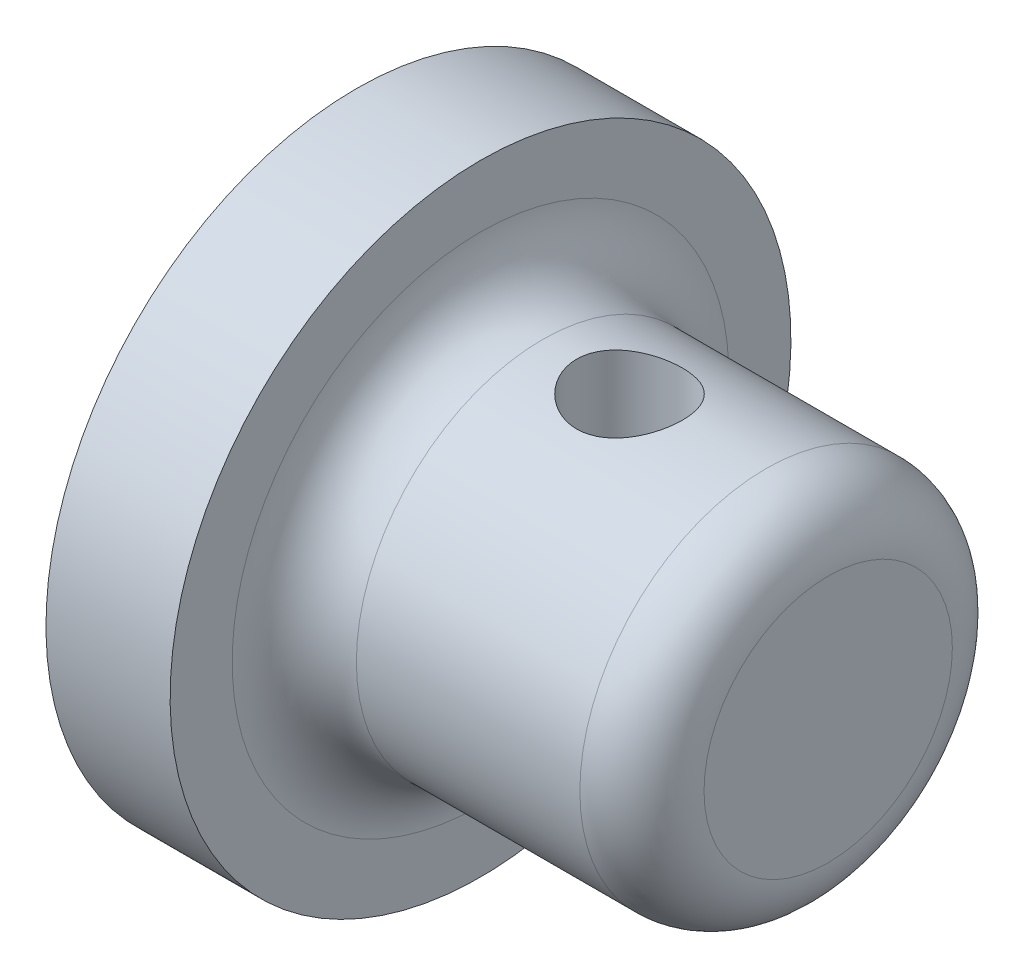
SolidWorks part; units mm, degrees
material "6061 Alloy"
ref_plane "Front Plane" through (0, 0, 0) normal (0, 0, 1) x (1, 0, 0)
ref_plane "Top Plane" through (0, 0, 0) normal (0, 1, 0) x (1, 0, 0)
ref_plane "Right Plane" through (0, 0, 0) normal (1, 0, 0) x (0, 0, -1)
sketch "Sketch1" plane through (0, 0, 0) normal (0, 0, 1) x (1, 0, 0)
  line L0 (0, 0) -> (0, 15.875)
  line L1 (0, 15.875) -> (6.35, 15.875)
  line L2 (6.35, 15.875) -> (6.35, 12.7)
  line L3 (9.525, 9.525) -> (20.955, 9.525)
  line L4 (24.13, 6.35) -> (24.13, 0)
  line L5 (24.13, 0) -> (0, 0)
  arc A0 (6.35, 12.7) -> (9.525, 9.525) centre (9.525, 12.7) ccw
  arc A1 (20.955, 9.525) -> (24.13, 6.35) centre (20.955, 6.35) cw
  dimension "D5" = 3.175
  dimension "D6" = 3.175
  dimension "D1" = 9.525
  dimension "D2" = 24.13
  dimension "D3" = 6.35
  dimension "D4" = 15.875
revolve "Revolve1" add sketch "Sketch1" angle 360 about L5
sketch "Sketch2" plane through (0, 0, 0) normal (-1, 0, 0) x (0, 0, 1)
  line L0 (-3.4856, 3.429) -> (3.4856, 3.429)
  arc A0 (-3.4856, 3.429) -> (3.4856, 3.429) centre (0, 0) ccw
  dimension "D1" = 9.779
  dimension "D2" = 3.429
extrude "Cut-Extrude1" cut sketch "Sketch2" against normal blind 19.304
ref_plane "Plane1" through (0, 9.525, 0) normal (0, 1, 0) x (1, 0, 0)
sketch "Sketch5" plane through (0, 9.525, 0) normal (0, 1, 0) x (1, 0, 0)
  point P0 (13.97, 0)
  dimension "D1" = 13.97
hole_wizard "1/4-28 Tapped Hole1" positions "Sketch5" profile "Sketch6" tap size "1/4-28" standard "ANSI Inch"
sketch "Sketch6" plane through (13.97, 9.525, 0) normal (1, 0, 0) x (0, 0, 1)
  line L0 (0, 0) -> (0, 6.096)
  line L1 (0, 6.096) -> (2.7051, 6.096)
  line L2 (2.7051, 6.096) -> (2.7051, 0)
  line L5 (2.7051, 0) -> (0, 0)
  line L11 (0, -6.35) -> (0, 107.95) construction
  dimension "Thru Tap Drill Dia." = 5.4102
  dimension "Thru Tap Drill Depth" = 6.096
cosmetic thread "Hole Thread1" parameters "D2"=6.35
